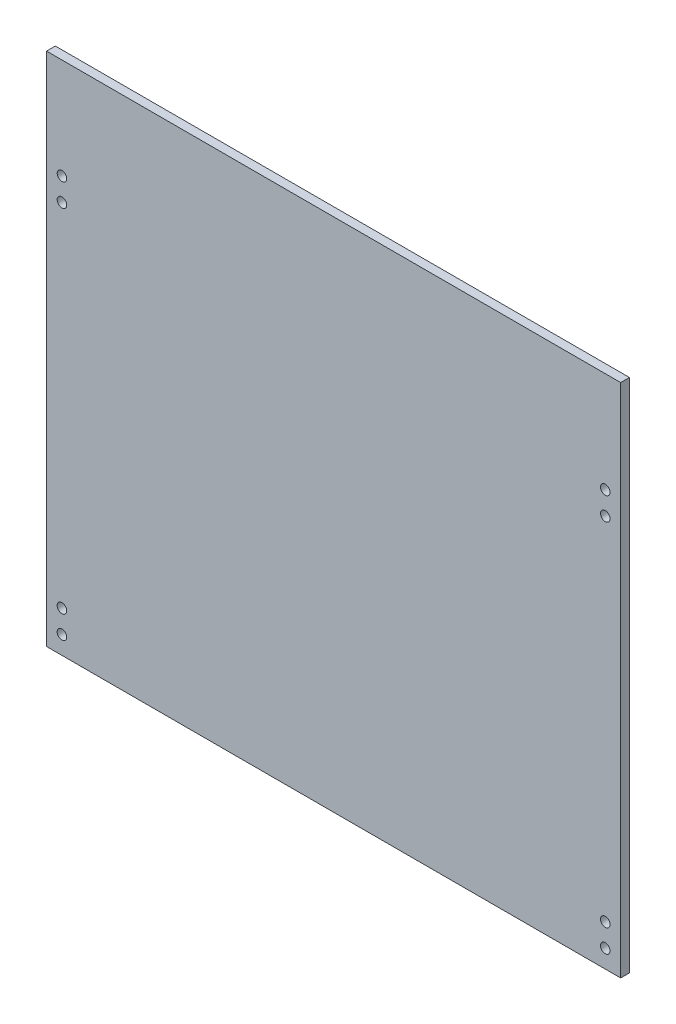
SolidWorks part; units mm, degrees
ref_plane "Front Plane" through (0, 0, 0) normal (0, 0, 1) x (1, 0, 0)
ref_plane "Top Plane" through (0, 0, 0) normal (0, 1, 0) x (1, 0, 0)
ref_plane "Right Plane" through (0, 0, 0) normal (1, 0, 0) x (0, 0, -1)
sketch "Sketch1" plane through (0, 0, 0) normal (0, 0, 1) x (1, 0, 0)
  line L1 (-73.1533, 40.2838) -> (142.8467, 40.2838)
  line L2 (-73.1533, 40.2838) -> (-73.1533, -153.7162)
  line L3 (-73.1533, -153.7162) -> (142.8467, -153.7162)
  line L4 (142.8467, 40.2838) -> (142.8467, -153.7162)
  circle A0 centre (-67.3533, -146.9162) radius 1.8
  circle A1 centre (-67.3533, -138.3162) radius 1.8
  circle A2 centre (-67.3533, -6.1162) radius 1.8
  circle A3 centre (137.0467, 2.4838) radius 1.8
  circle A4 centre (137.0467, -146.9162) radius 1.8
  circle A5 centre (137.0467, -138.3162) radius 1.8
  circle A6 centre (137.0467, -6.1162) radius 1.8
  circle A7 centre (-67.3533, 2.4838) radius 1.8
  point P20 (0, 0)
  point P21 (0, 0)
  point P22 (0, 0)
  point P23 (0, 0)
  point P24 (0, 0)
  point P25 (0, 0)
  point P26 (0, 0)
  point P27 (0, 0)
  dimension "D3" = 6.8
  dimension "D1" = 216
  dimension "D2" = 194
  dimension "D4" = 8.6
  dimension "D5" = 5.8
  dimension "D6" = 37.8
  dimension "D7" = 5.8
  dimension "D8" = 5.8
  dimension "D9" = 46.4
  dimension "D10" = 5.8
extrude "Boss-Extrude1" add sketch "Sketch1" along normal blind 3.302
